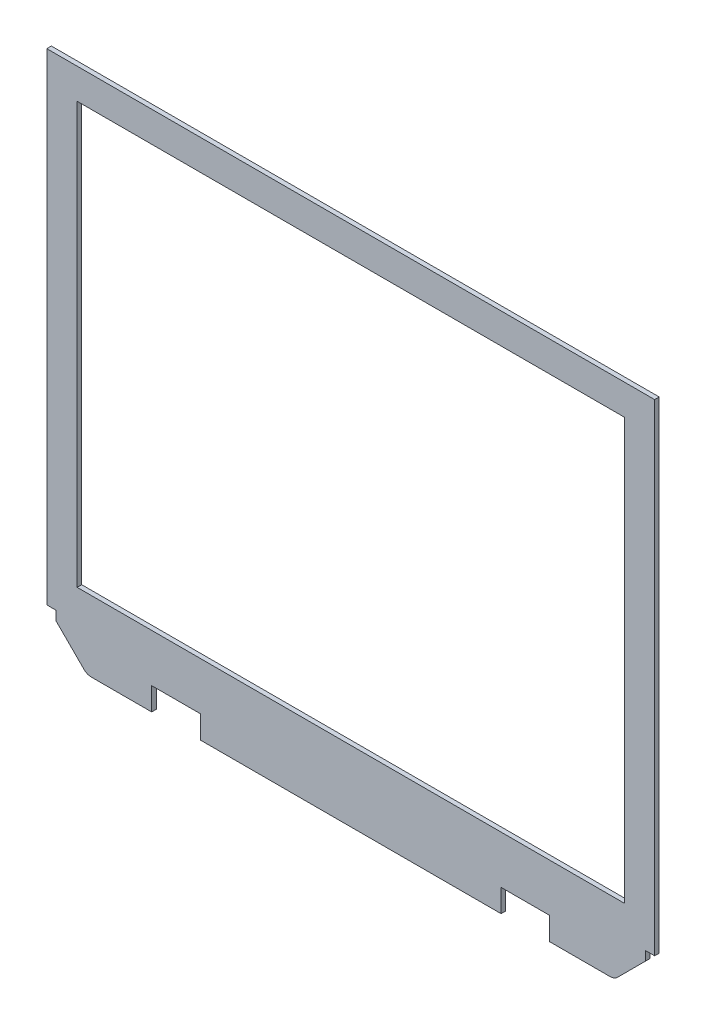
SolidWorks part; units mm, degrees
material "Acrylic (Medium-high impact)"
ref_plane "Front Plane" through (0, 0, 0) normal (0, 0, 1) x (1, 0, 0)
ref_plane "Top Plane" through (0, 0, 0) normal (0, 1, 0) x (1, 0, 0)
ref_plane "Right Plane" through (0, 0, 0) normal (1, 0, 0) x (0, 0, -1)
sketch "Sketch1" plane through (0, 0, 0) normal (0, 0, 1) x (1, 0, 0)
  line L0 (-180, 138.5) -> (180, 138.5)
  line L1 (-200, -158.5) -> (200, -158.5)
  line L2 (-200, -158.5) -> (-200, 158.5)
  line L3 (-200, 158.5) -> (200, 158.5)
  line L4 (200, -158.5) -> (200, 158.5)
  line L5 (-200, -158.5) -> (200, 158.5) construction
  line L6 (-200, 158.5) -> (200, -158.5) construction
  line L7 (180, -138.5) -> (180, 138.5)
  line L8 (-180, -138.5) -> (180, -138.5)
  line L9 (-180, -138.5) -> (-180, 138.5)
  point P0 (0, 0)
  dimension "D1" = 400
  dimension "D2" = 317
  dimension "D3" = 20
extrude "Boss-Extrude1" add sketch "Sketch1" along normal blind 3
sketch "Sketch2" plane through (0, 0, 3) normal (0, 0, 1) x (1, 0, 0)
  line L0 (0, -1158.5) -> (0, 48841.5) construction
  line L1 (-200, -158.5) -> (200, -158.5) construction
  line L2 (130.9553, -185) -> (170.4338, -185)
  line L3 (-194, -158.5) -> (194, -158.5)
  line L4 (0, -158.5) -> (0, -185)
  line L5 (-98.9553, -185) -> (98.9553, -185)
  line L7 (194, -164.5) -> (175.3836, -183.1164)
  line L8 (194, -164.5) -> (194, -158.5)
  line L10 (98.9553, -185) -> (98.9553, -170)
  line L11 (98.9553, -170) -> (130.9553, -170)
  line L12 (130.9553, -185) -> (130.9553, -170)
  line L13 (-130.9553, -185) -> (-130.9553, -170)
  line L14 (-98.9553, -170) -> (-130.9553, -170)
  line L15 (-98.9553, -185) -> (-98.9553, -170)
  line L16 (-194, -164.5) -> (-194, -158.5)
  line L17 (-194, -164.5) -> (-175.3836, -183.1164)
  line L18 (-130.9553, -185) -> (-170.4338, -185)
  arc A0 (-170.4338, -185) -> (-175.3836, -183.1164) centre (-170.6041, -178.0021) cw
  arc A1 (170.4338, -185) -> (175.3836, -183.1164) centre (170.6041, -178.0021) ccw
  point P5 (0, -158.5)
  point P13 (194, -161.5)
  point P14 (0, -171.75)
  line M12 (-200, -158.5) -> (200, -158.5)
  dimension "D7" = 7
  dimension "D1" = 6
  dimension "D2" = 26.5
  dimension "D3" = 19.5021
  dimension "D4" = 26.3276
  dimension "D5" = 23.3959
  dimension "D6" = 170.6041
  dimension "D8" = 32
  dimension "D9" = 15
  dimension "D10" = 71.6488
extrude "Boss-Extrude4" add sketch "Sketch2" against normal through all contours A0 L18 L13 L14 L15 L5 L4 L16 L17 M12 | L2 A1 L7 L8 L3 L4 L5 L10 L11 L12
